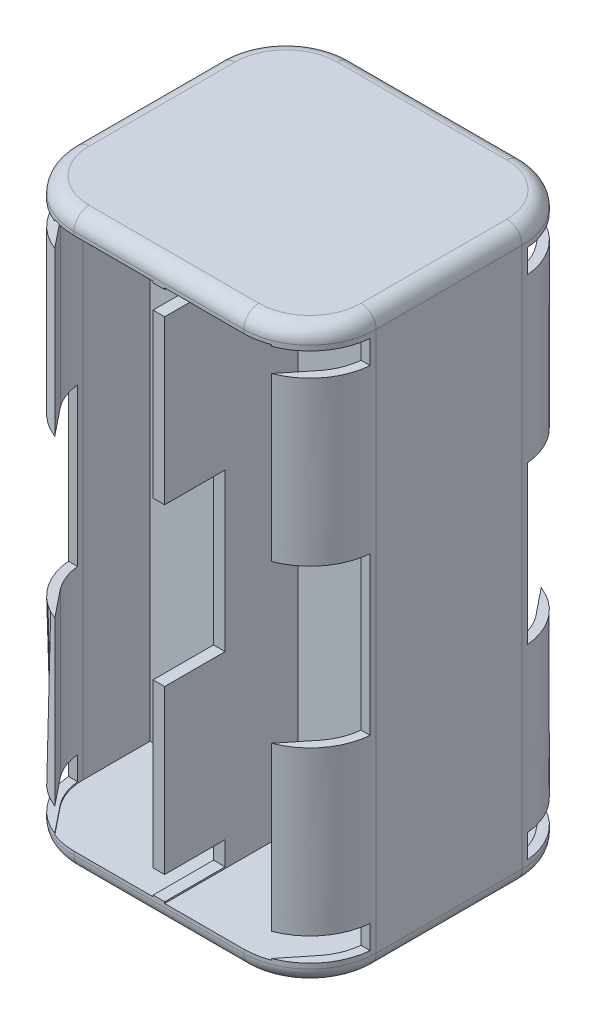
SolidWorks part; units mm, degrees
ref_plane "Front Plane" through (0, 0, 0) normal (0, 0, 1) x (1, 0, 0)
ref_plane "Top Plane" through (0, 0, 0) normal (0, 1, 0) x (1, 0, 0)
ref_plane "Right Plane" through (0, 0, 0) normal (1, 0, 0) x (0, 0, -1)
sketch "Sketch1" plane through (0, 0, 0) normal (0, 1, 0) x (1, 0, 0)
  line L0 (15, 13.81) -> (-15, -13.81) construction
  line L1 (-15, 13.81) -> (15, 13.81) construction
  line L2 (-15, 13.81) -> (-15, -13.81) construction
  line L3 (-15, -13.81) -> (15, -13.81) construction
  line L4 (15, 13.81) -> (15, -13.81) construction
  line L5 (-15, 13.81) -> (15, -13.81) construction
  line L6 (-8.425, 13.81) -> (8.425, 13.81)
  line L7 (-15, 7.235) -> (-15, -7.235)
  line L8 (-8.425, -13.81) -> (8.425, -13.81)
  line L9 (15, 7.235) -> (15, -7.235)
  arc A0 (-15, 7.235) -> (-8.425, 13.81) centre (-8.425, 7.235) cw
  arc A1 (-8.425, -13.81) -> (-15, -7.235) centre (-8.425, -7.235) cw
  arc A2 (8.425, -13.81) -> (15, -7.235) centre (8.425, -7.235) ccw
  arc A3 (15, 7.235) -> (8.425, 13.81) centre (8.425, 7.235) ccw
  dimension "D3" = 16.85
  dimension "D1" = 30
  dimension "D2" = 27.62
extrude "Boss-Extrude1" add sketch "Sketch1" along normal mid plane 56.63
sketch "Sketch2" plane through (0, -28.315, 0) normal (0, -1, 0) x (1, 0, 0)
  line L1 (-0.8919, 9.9191) -> (0.5255, 9.9191)
  line L2 (-0.8919, 9.9191) -> (-0.8919, 5.5992)
  line L3 (-0.8919, 5.5992) -> (0.5255, 5.5992)
  line L4 (0.5255, 9.9191) -> (0.5255, 5.5992)
  circle A0 centre (6.9379, 6.6117) radius 3.2582
fillet "Fillet1" radius 1.5 16 edges at (0, 28.315, -13.81) (13.0742, 28.315, -11.8842) (15, 28.315, 0) (13.0742, 28.315, 11.8842) (0, 28.315, 13.81) (-13.0742, 28.315, 11.8842) (-15, 28.315, 0) (-13.0742, 28.315, -11.8842) (-15, -28.315, 0) (-13.0742, -28.315, 11.8842) (0, -28.315, 13.81) (13.0742, -28.315, 11.8842) (15, -28.315, 0) (13.0742, -28.315, -11.8842) (0, -28.315, -13.81) (-13.0742, -28.315, -11.8842)
sketch "Sketch4" plane through (0, -28.315, 0) normal (0, -1, 0) x (1, 0, 0)
  line L0 (2.325, 2.325) -> (-2.325, -2.325) construction
  line L1 (-2.325, 2.325) -> (2.325, 2.325) construction
  line L2 (-2.325, 2.325) -> (-2.325, -2.325) construction
  line L3 (-2.325, -2.325) -> (2.325, -2.325) construction
  line L4 (2.325, 2.325) -> (2.325, -2.325) construction
  line L5 (-2.325, 2.325) -> (-3.575, 2.325) construction
  line L6 (2.325, 2.325) -> (3.575, 2.325) construction
  circle A0 centre (-2.325, 2.325) radius 1.25
  circle A1 centre (2.325, 2.325) radius 1.25
  circle A3 centre (2.325, -2.325) radius 1.25
  circle A4 centre (-2.325, -2.325) radius 1.25
  dimension "D1" = 2.5
  dimension "D2" = 7.15
sketch "Sketch5" plane through (0, 28.315, 0) normal (0, 1, 0) x (1, 0, 0)
  circle A0 centre (-2.325, 2.325) radius 1.25 construction
  circle A1 centre (2.325, 2.325) radius 1.25 construction
  circle A2 centre (2.325, -2.325) radius 1.25 construction
  circle A3 centre (-2.325, -2.325) radius 1.25 construction
  circle A4 centre (-2.325, 2.325) radius 1.25
  circle A5 centre (2.325, 2.325) radius 1.25
  circle A6 centre (2.325, -2.325) radius 1.25
  circle A7 centre (-2.325, -2.325) radius 1.25
sketch "Sketch6" plane through (0, 0, 0) normal (0, 1, 0) x (1, 0, 0)
  line L0 (0, 0) -> (0, -13.81) construction
  line L1 (8.425, -13.81) -> (-8.425, -13.81) construction
  line L2 (0, 0) -> (-15, 0) construction
  line L3 (-15, -7.235) -> (-15, 7.235) construction
  line L4 (0.575, -7.235) -> (14.1, -7.235) construction
  line L5 (-0.575, -0.575) -> (-14.1, -0.575)
  line L6 (-0.575, -0.575) -> (-0.575, -7.235)
  line L7 (-0.575, -7.235) -> (-14.1, -7.235) construction
  line L8 (-14.1, -0.575) -> (-14.1, -7.235)
  line L9 (14.1, -0.575) -> (14.1, -7.235)
  line L10 (0.575, -0.575) -> (14.1, -0.575)
  line L11 (0.575, -0.575) -> (0.575, -7.235)
  line L12 (0.575, 0.575) -> (0.575, 7.235)
  line L13 (0.575, 0.575) -> (14.1, 0.575)
  line L14 (14.1, 0.575) -> (14.1, 7.235)
  line L15 (-14.1, 0.575) -> (-14.1, 7.235)
  line L16 (-0.575, 7.235) -> (-14.1, 7.235) construction
  line L17 (-0.575, 0.575) -> (-0.575, 7.235)
  line L18 (-0.575, 0.575) -> (-14.1, 0.575)
  line L19 (0.575, 7.235) -> (14.1, 7.235) construction
  line L20 (0.575, -0.575) -> (-0.575, -0.575) construction
  line L21 (-0.575, -0.575) -> (-0.575, 0.575) construction
  line L22 (-13, -10.5928) -> (-8.8666, -15.7486)
  line L23 (0, -10.5928) -> (-13, -10.5928) construction
  line L24 (-0.575, -7.235) -> (-0.575, -15.7486)
  line L25 (-0.575, -15.7486) -> (-8.8666, -15.7486)
  line L26 (0.575, -7.235) -> (0.575, -15.7486)
  line L27 (0.575, -15.7486) -> (8.8666, -15.7486)
  line L28 (13, -10.5928) -> (8.8666, -15.7486)
  line L29 (13, 10.5928) -> (8.8666, 15.7486)
  line L30 (0.575, 15.7486) -> (8.8666, 15.7486)
  line L31 (0.575, 7.235) -> (0.575, 15.7486)
  line L32 (-0.575, 7.235) -> (-0.575, 15.7486)
  line L33 (-0.575, 15.7486) -> (-8.8666, 15.7486)
  line L34 (-13, 10.5928) -> (-8.8666, 15.7486)
  arc A0 (-14.1, -7.235) -> (-13, -10.5928) centre (-8.425, -7.235) ccw
  arc A1 (-15, -7.235) -> (-8.425, -13.81) centre (-8.425, -7.235) ccw construction
  arc A2 (14.1, -7.235) -> (13, -10.5928) centre (8.425, -7.235) cw
  arc A3 (14.1, 7.235) -> (13, 10.5928) centre (8.425, 7.235) ccw
  arc A4 (-14.1, 7.235) -> (-13, 10.5928) centre (-8.425, 7.235) cw
  dimension "D1" = 1.15
  dimension "D2" = 0.9
  dimension "D4" = 13
extrude "Cut-Extrude2" cut sketch "Sketch6" along normal offset from surface 1.85 and the other way offset from surface (26.465 mm away) 1.85 up to face at (0, 28.315, 0) other way up to face at (0, -28.315, 0)
sketch "Sketch7" plane through (0, 0, 0) normal (1, 0, 0) x (0, 0, -1)
  line L0 (7.81, 0) -> (-7.81, 0) construction
  line L1 (-16.6735, -7.8111) -> (-7.81, -7.8111)
  line L2 (-16.6735, -7.8111) -> (-16.6735, 7.8111)
  line L3 (-16.6735, 7.8111) -> (-7.81, 7.8111)
  line L4 (-7.81, -7.8111) -> (-7.81, 7.8111)
  line L5 (0, 0) -> (0, 19.4182) construction
  line L6 (7.81, -7.8111) -> (7.81, 7.8111)
  line L7 (16.6735, 7.8111) -> (7.81, 7.8111)
  line L8 (16.6735, -7.8111) -> (16.6735, 7.8111)
  line L9 (16.6735, -7.8111) -> (7.81, -7.8111)
  line L10 (-7.235, -26.815) -> (7.235, -26.815) construction
  line L11 (-7.81, -23.9775) -> (-16.6735, -23.9775)
  line L12 (-7.81, -23.9775) -> (-7.81, -26.315)
  line L13 (-7.81, -26.315) -> (-16.6735, -26.315)
  line L14 (-16.6735, -23.9775) -> (-16.6735, -26.315)
  line L15 (-16.6735, 23.9775) -> (-16.6735, 26.315)
  line L16 (-7.81, 26.315) -> (-16.6735, 26.315)
  line L17 (-7.81, 23.9775) -> (-7.81, 26.315)
  line L18 (-7.81, 23.9775) -> (-16.6735, 23.9775)
  line L19 (7.81, 23.9775) -> (16.6735, 23.9775)
  line L20 (7.81, 23.9775) -> (7.81, 26.315)
  line L21 (7.81, 26.315) -> (16.6735, 26.315)
  line L22 (16.6735, 23.9775) -> (16.6735, 26.315)
  line L23 (16.6735, -23.9775) -> (16.6735, -26.315)
  line L24 (7.81, -26.315) -> (16.6735, -26.315)
  line L25 (7.81, -23.9775) -> (7.81, -26.315)
  line L26 (7.81, -23.9775) -> (16.6735, -23.9775)
  line L27 (-13.81, 26.465) -> (-13.81, -26.465) construction
  point P7 (0, 0)
  dimension "D1" = 0.5
  dimension "D2" = 6
extrude "Cut-Extrude3" cut sketch "Sketch7" against normal through all both and the other way through all
scale "Scale1" bodies to scale 105 scale about centroid uniform scaling yes scale factor 0.3478
